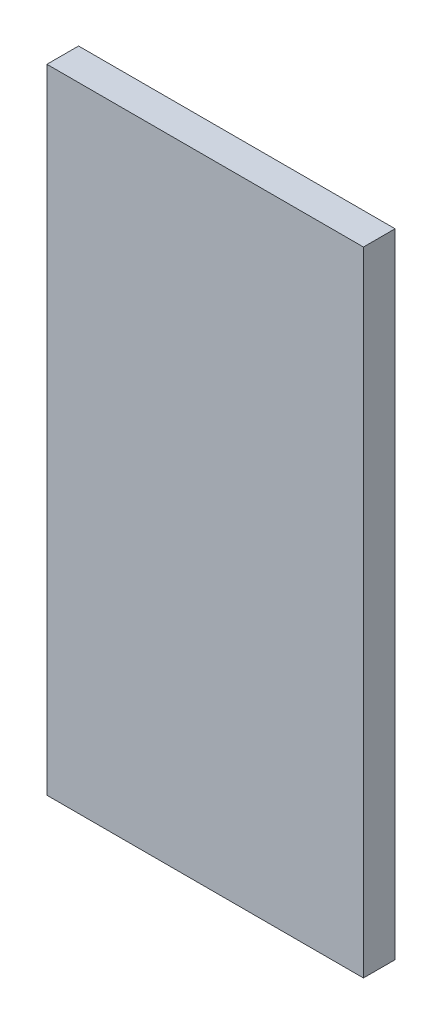
SolidWorks part; units mm, degrees
ref_plane "Спереди" through (0, 0, 0) normal (0, 0, 1) x (1, 0, 0)
ref_plane "Сверху" through (0, 0, 0) normal (0, 1, 0) x (1, 0, 0)
ref_plane "Справа" through (0, 0, 0) normal (1, 0, 0) x (0, 0, -1)
sketch "Эскиз1" plane through (0, 0, 0) normal (0, 0, 1) x (1, 0, 0)
  line L1 (-17.3755, 575.7521) -> (282.6245, 575.7521)
  line L2 (-17.3755, 575.7521) -> (-17.3755, -24.2479)
  line L3 (-17.3755, -24.2479) -> (282.6245, -24.2479)
  line L4 (282.6245, 575.7521) -> (282.6245, -24.2479)
extrude "Бобышка-Вытянуть1" add sketch "Эскиз1" along normal blind 30
